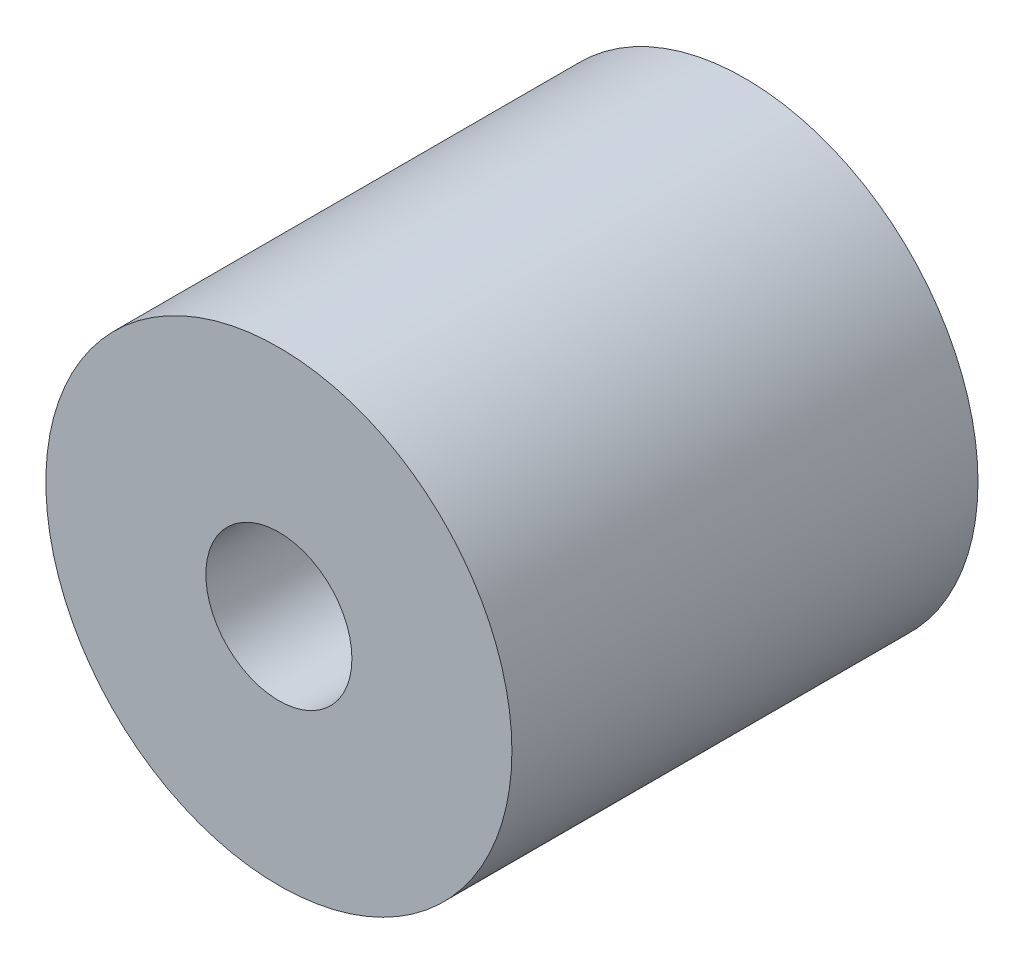
SolidWorks part; units mm, degrees
ref_plane "Piano frontale" through (0, 0, 0) normal (0, 0, 1) x (1, 0, 0)
ref_plane "Piano superiore" through (0, 0, 0) normal (0, 1, 0) x (1, 0, 0)
ref_plane "Piano destro" through (0, 0, 0) normal (1, 0, 0) x (0, 0, -1)
sketch "Schizzo1" plane through (0, 0, 0) normal (0, 0, 1) x (1, 0, 0)
  circle A0 centre (0, 0) radius 2.5
  circle A1 centre (0, 0) radius 7.5
  dimension "D1" = 5
  dimension "D2" = 5
extrude "Estrusione-Estrusione1" add sketch "Schizzo1" along normal blind 15
sketch "Schizzo2" plane through (0, 0, 0) normal (0, 0, -1) x (-1, 0, 0)
  line L1 (-2, -1.5) -> (2, -1.5)
  line L3 (-2, 1.5) -> (2, 1.5)
  line L4 (-2.5, 1.5) -> (2.5, 1.5) construction
  line L5 (-2.5, 0) -> (2.5, 0) construction
  line L6 (-2.5, -1.5) -> (2.5, -1.5) construction
  arc A2 (-2, -1.5) -> (2, -1.5) centre (0, 0) ccw
  arc A3 (2, 1.5) -> (-2, 1.5) centre (0, 0) ccw
  dimension "D1" = 1.5
  dimension "D2" = 1.5
extrude "Estrusione-Estrusione2" add sketch "Schizzo2" against normal blind 6
sketch "Schizzo3" plane through (0, 0, 15) normal (0, 0, 1) x (1, 0, 0)
  circle A0 centre (0, 0) radius 2.35
  circle A1 centre (0, 0) radius 2.5
  dimension "D1" = 4.7
extrude "Estrusione-Estrusione3" add sketch "Schizzo3" against normal up to surface (9 mm away) up to face at (0, -2, 6)
